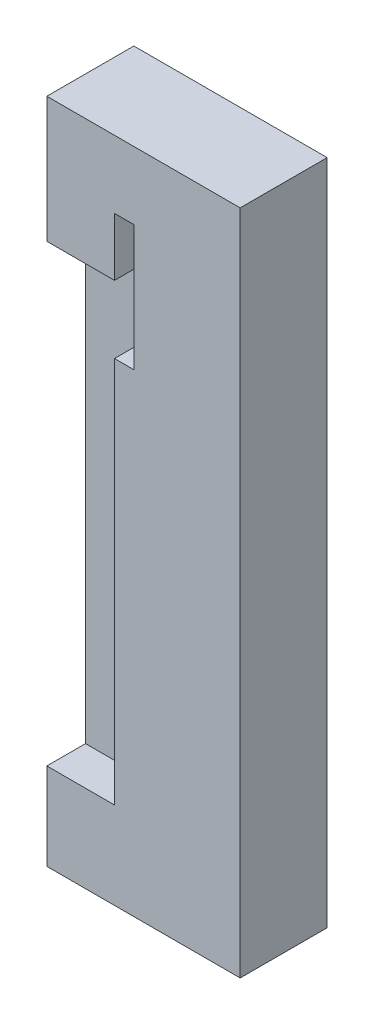
SolidWorks part; units mm, degrees
ref_plane "Plan de face" through (0, 0, 0) normal (0, 0, 1) x (1, 0, 0)
ref_plane "Plan de dessus" through (0, 0, 0) normal (0, 1, 0) x (1, 0, 0)
ref_plane "Plan de droite" through (0, 0, 0) normal (1, 0, 0) x (0, 0, -1)
sketch "Esquisse1" plane through (0, 0, 0) normal (0, 0, 1) x (1, 0, 0)
  line L1 (-15.9031, 5.0885) -> (4.0969, 5.0885)
  line L2 (-15.9031, 5.0885) -> (-15.9031, -63.9115)
  line L3 (-15.9031, -63.9115) -> (4.0969, -63.9115)
  line L4 (4.0969, 5.0885) -> (4.0969, -63.9115)
  dimension "D1" = 69
  dimension "D2" = 20
extrude "Extrusion1" add sketch "Esquisse1" along normal blind 9
sketch "Esquisse2" plane through (0, 0, 9) normal (0, 0, 1) x (1, 0, 0)
  line L0 (-28.9031, -7.9115) -> (-8.9031, -7.9115) construction
  line L1 (-8.9031, -54.9115) -> (-15.9031, -54.9115)
  line L2 (-8.9031, -54.9115) -> (-8.9031, -7.9115)
  line L3 (-8.9031, -7.9115) -> (-15.9031, -7.9115)
  line L4 (-15.9031, -54.9115) -> (-15.9031, -7.9115)
  line L5 (-15.9031, 5.0885) -> (-15.9031, -63.9115) construction
extrude "Enlèv. mat.-Extru.1" cut sketch "Esquisse2" against normal blind 4
sketch "Esquisse3" plane through (0, 0, 9) normal (0, 0, 1) x (1, 0, 0)
  line L2 (-8.9031, -1.9115) -> (-6.9031, -1.9115)
  line L3 (-8.9031, -1.9115) -> (-8.9031, -14.9115)
  line L4 (-8.9031, -14.9115) -> (-6.9031, -14.9115)
  line L6 (-6.9031, -1.9115) -> (-6.9031, -14.9115)
extrude "Enlèv. mat.-Extru.2" cut sketch "Esquisse3" against normal blind 5
